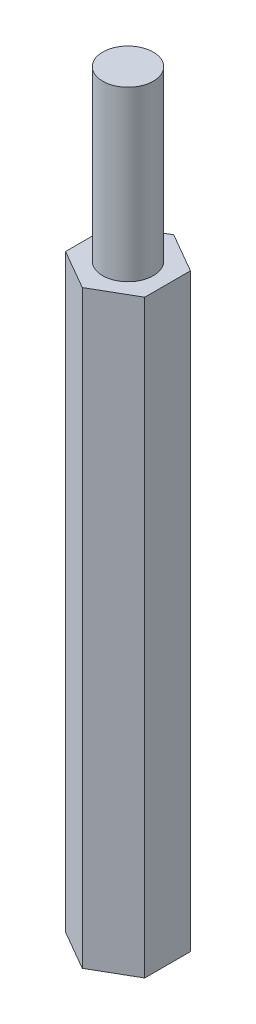
SolidWorks part; units mm, degrees
other "Markup1"
sketch "Sketch6" plane through (2.35, 45, 2.7135) normal (0.424, 0.6635, 0.6165) x (0.8139, 0.0195, -0.5807)
sketch "Sketch7" plane through (2.35, 45, 2.7135) normal (0.424, 0.6635, 0.6165) x (0.8139, 0.0195, -0.5807)
sketch "Sketch8" plane through (2.35, 45, 2.7135) normal (0.424, 0.6635, 0.6165) x (0.8139, 0.0195, -0.5807)
material "Brass"
ref_plane "Front Plane" through (0, 0, 0) normal (0, 0, 1) x (1, 0, 0)
ref_plane "Top Plane" through (0, 0, 0) normal (0, 1, 0) x (1, 0, 0)
ref_plane "Right Plane" through (0, 0, 0) normal (1, 0, 0) x (0, 0, -1)
sketch "Sketch1" plane through (0, 0, 0) normal (0, 1, 0) x (1, 0, 0)
  line L1 (0, 2.7135) -> (-2.35, 1.3568)
  line L2 (-2.35, 1.3568) -> (-2.35, -1.3568)
  line L3 (-2.35, -1.3568) -> (0, -2.7135)
  line L4 (0, -2.7135) -> (2.35, -1.3568)
  line L5 (2.35, -1.3568) -> (2.35, 1.3568)
  line L6 (2.35, 1.3568) -> (0, 2.7135)
  circle A0 centre (0, 0) radius 2.35 construction
  dimension "D1" = 4.7
extrude "Boss-Extrude1" add sketch "Sketch1" along normal blind 35
sketch "Sketch2" plane through (0, 35, 0) normal (0, 1, 0) x (1, 0, 0)
  circle A0 centre (0, 0) radius 1.5
  dimension "D1" = 3
extrude "Boss-Extrude2" add sketch "Sketch2" along normal blind 10
sketch "Sketch5" plane through (0, 0, 0) normal (0, -1, 0) x (1, 0, 0)
  circle A0 centre (0, 0) radius 1.5
  dimension "D1" = 3
extrude "Cut-Extrude1" cut sketch "Sketch5" against normal blind 10
